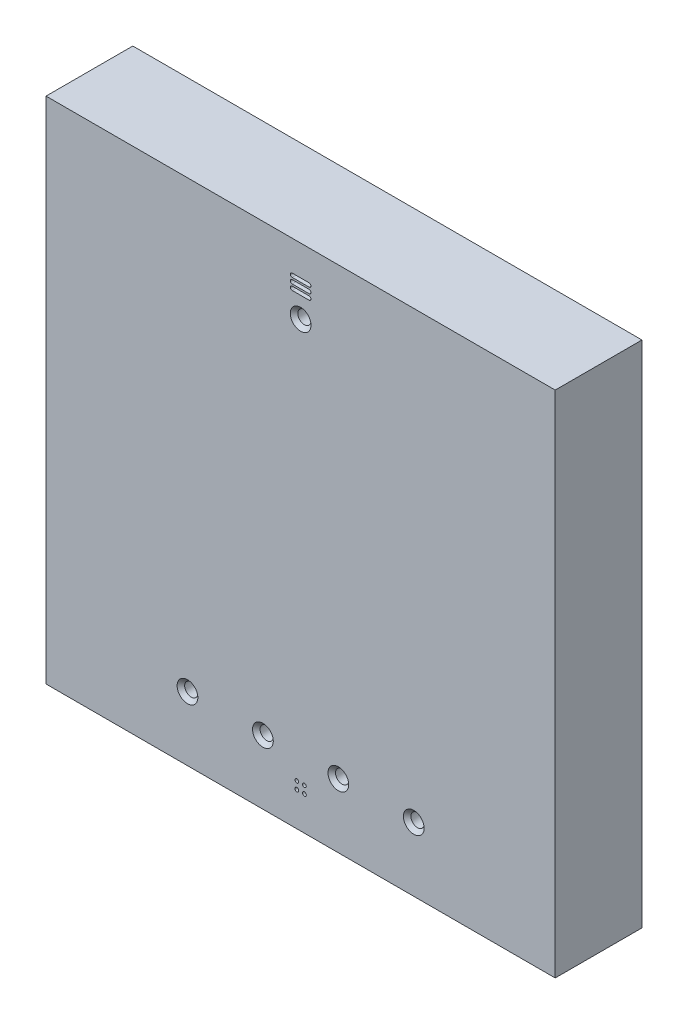
SolidWorks part; units mm, degrees
ref_plane "Ebene vorne" through (0, 0, 0) normal (0, 0, 1) x (1, 0, 0)
ref_plane "Ebene oben" through (0, 0, 0) normal (0, 1, 0) x (1, 0, 0)
ref_plane "Ebene rechts" through (0, 0, 0) normal (1, 0, 0) x (0, 0, -1)
sketch "Skizze1" plane through (0, 0, 0) normal (0, 0, 1) x (1, 0, 0)
  line L0 (67.5, 67.5) -> (-67.5, 67.5) construction
  line L1 (-67.5, 67.5) -> (-67.5, -67.5) construction
  line L2 (67.5, -67.5) -> (67.5, 67.5) construction
  line L3 (-67.5, -67.5) -> (67.5, -67.5) construction
  line L4 (67.5, 67.5) -> (-67.5, 67.5)
  line L5 (-67.5, 67.5) -> (-67.5, -67.5)
  line L6 (67.5, -67.5) -> (67.5, 67.5)
  line L7 (-67.5, -67.5) -> (67.5, -67.5)
  line L8 (65.5, 65.5) -> (-65.5, 65.5)
  line L9 (-65.5, 65.5) -> (-65.5, -65.5)
  line L10 (-65.5, -65.5) -> (65.5, -65.5)
  line L11 (65.5, -65.5) -> (65.5, 65.5)
  dimension "D1" = 2
extrude "Aufsatz-Linear austragen1" add sketch "Skizze1" along normal blind 18
sketch "Skizze2" plane through (0, 0, 18) normal (0, 0, 1) x (1, 0, 0)
  line L0 (-67.5, 67.5) -> (-67.5, -67.5) construction
  line L1 (-67.5, -67.5) -> (67.5, -67.5) construction
  line L2 (67.5, -67.5) -> (67.5, 67.5) construction
  line L3 (67.5, 67.5) -> (-67.5, 67.5) construction
  line L4 (-67.5, 67.5) -> (-67.5, -67.5)
  line L5 (-67.5, -67.5) -> (67.5, -67.5)
  line L6 (67.5, -67.5) -> (67.5, 67.5)
  line L7 (67.5, 67.5) -> (-67.5, 67.5)
extrude "Aufsatz-Linear austragen2" add sketch "Skizze2" along normal blind 5
extrude "Schnitt-Linear austragen1" cut sketch "Skizze3" against normal blind 11
sketch "Skizze3" plane through (-67.5, 0, 0) normal (-1, 0, 0) x (0, 0, 1)
  line L3 (5, -33.149) -> (3, -33.149)
  line L4 (3, -33.149) -> (3, -41.849)
  line L5 (3, -41.849) -> (5, -41.849)
  line L6 (5, -33.149) -> (7.4, -33.149)
  line L8 (5, -41.849) -> (7.4, -41.849)
  line L9 (7.4, -41.849) -> (7.4, -33.149)
extrude "Schnitt-Linear austragen2" cut sketch "Skizze4" against normal blind 10
sketch "Skizze4" plane through (0, 0, 23) normal (0, 0, 1) x (1, 0, 0)
  line L0 (-2.25, 56) -> (2.25, 56) construction
  line L1 (-2.25, 56.5) -> (2.25, 56.5)
  line L2 (-2.25, 55.5) -> (2.25, 55.5)
  line L3 (-2.25, 57.5) -> (2.25, 57.5) construction
  line L4 (-2.25, 58) -> (2.25, 58)
  line L5 (-2.25, 57) -> (2.25, 57)
  line L6 (-2.25, 59) -> (2.25, 59) construction
  line L7 (-2.25, 59.5) -> (2.25, 59.5)
  line L8 (-2.25, 58.5) -> (2.25, 58.5)
  arc A0 (-2.25, 56.5) -> (-2.25, 55.5) centre (-2.25, 56) ccw
  circle A1 centre (0, 50) radius 1.75
  circle A2 centre (30, -50.5) radius 1.75
  circle A3 centre (10, -50.5) radius 1.75
  circle A4 centre (-10, -50.5) radius 1.75
  circle A5 centre (-30, -50.5) radius 1.75
  arc A6 (2.25, 55.5) -> (2.25, 56.5) centre (2.25, 56) ccw
  arc A7 (-2.25, 58) -> (-2.25, 57) centre (-2.25, 57.5) ccw
  arc A8 (2.25, 57) -> (2.25, 58) centre (2.25, 57.5) ccw
  arc A9 (-2.25, 59.5) -> (-2.25, 58.5) centre (-2.25, 59) ccw
  arc A10 (2.25, 58.5) -> (2.25, 59.5) centre (2.25, 59) ccw
  circle A11 centre (1, -56.5) radius 0.5
  circle A12 centre (1, -58.5) radius 0.5
  circle A13 centre (-1, -58.5) radius 0.5
  circle A14 centre (-1, -56.5) radius 0.5
  point P17 (0, 56)
  point P22 (0, -57.5)
  point P25 (0, 57.5)
  point P32 (0, 59)
  point P48 (0, -57.5)
chamfer "Fase1" distance 1 angle 45 4 edges at (11.75, -50.5, 23) (-8.25, -50.5, 23) (-28.25, -50.5, 23) (1.75, 50, 23)
